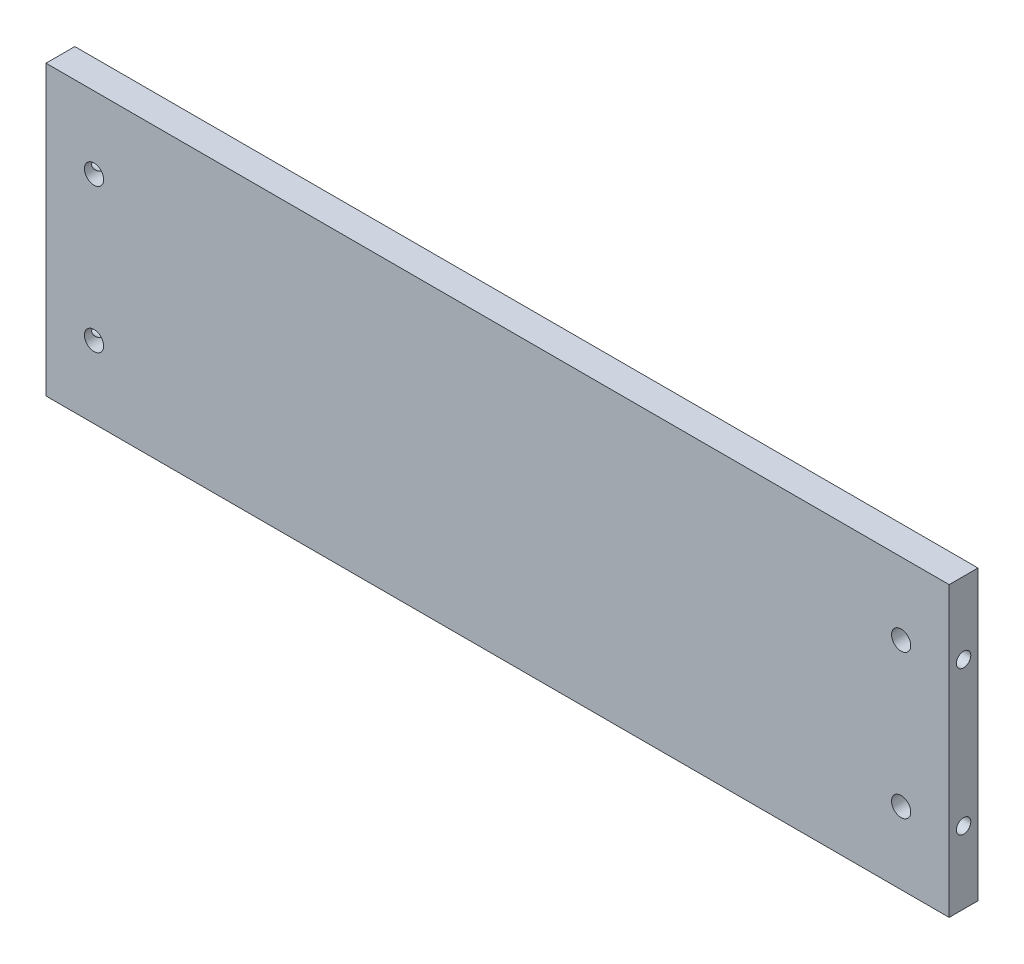
SolidWorks part; units mm, degrees
material "Beech"
ref_plane "Front Plane" through (0, 0, 0) normal (0, 0, 1) x (1, 0, 0)
ref_plane "Top Plane" through (0, 0, 0) normal (0, 1, 0) x (1, 0, 0)
ref_plane "Right Plane" through (0, 0, 0) normal (1, 0, 0) x (0, 0, -1)
sketch "Sketch1" plane through (0, 0, 0) normal (0, 0, 1) x (1, 0, 0)
  line L1 (-188, -60) -> (188, -60)
  line L2 (-188, -60) -> (-188, 60)
  line L3 (-188, 60) -> (188, 60)
  line L4 (188, -60) -> (188, 60)
  line L5 (-188, -60) -> (188, 60) construction
  line L6 (-188, 60) -> (188, -60) construction
  point P0 (0, 0)
  dimension "D1" = 120
  dimension "D2" = 376
extrude "Boss-Extrude1" add sketch "Sketch1" along normal blind 12
sketch "Sketch2" plane through (0, 0, 12) normal (0, 0, 1) x (1, 0, 0)
  line L0 (-199.8429, 0) -> (202.4794, 0) construction
  line L1 (-188, 60) -> (-188, -60) construction
  circle A0 centre (-168, 30) radius 4
  circle A1 centre (-168, -30) radius 4
  dimension "D1" = 8
  dimension "D2" = 8
  dimension "D3" = 30
  dimension "D4" = 30
  dimension "D5" = 20
  dimension "D6" = 20
extrude "Cut-Extrude1" cut sketch "Sketch2" against normal up to next
sketch "Sketch3" plane through (-188, 0, 0) normal (-1, 0, 0) x (0, 0, 1)
  line L0 (6, 50.3198) -> (6, -51.9196) construction
  line L1 (0, 60) -> (0, -60) construction
  circle A0 centre (6, 30) radius 3
  circle A1 centre (6, -30) radius 3
  point P6 (0, 0)
  point P9 (0, 0)
  dimension "D1" = 6
  dimension "D2" = 6
  dimension "D3" = 30
  dimension "D4" = 30
extrude "Cut-Extrude2" cut sketch "Sketch3" against normal up to next
mirror "Mirror1" about plane through (0, 0, 0) normal (1, 0, 0) of "Cut-Extrude2", "Cut-Extrude1"
